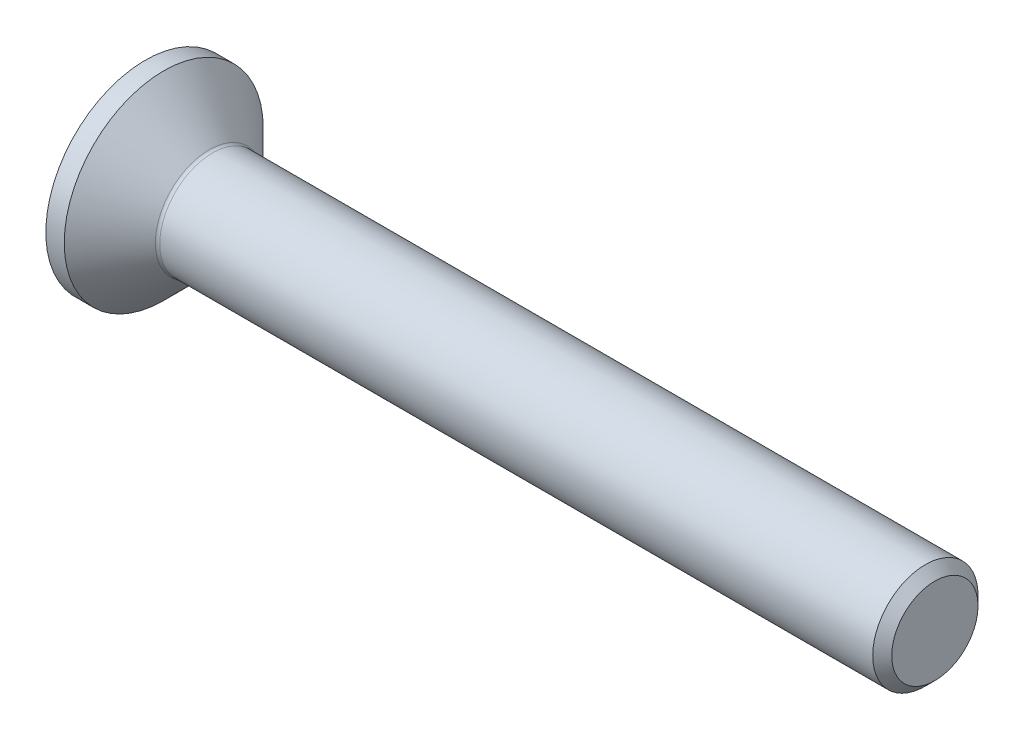
SolidWorks part; units mm, degrees
ref_plane "Front" through (0, 0, 0) normal (0, 0, 1) x (1, 0, 0)
ref_plane "Top" through (0, 0, 0) normal (0, 1, 0) x (1, 0, 0)
ref_plane "Right" through (0, 0, 0) normal (1, 0, 0) x (0, 0, -1)
sketch "Sketch1" plane through (0, 0, 0) normal (0, 0, 1) x (1, 0, 0)
  line L0 (0, 0) -> (0, 6.72)
  line L1 (0, 6.72) -> (3.72, 3)
  line L2 (3.72, 3) -> (45, 3)
  line L3 (45, 3) -> (45, 0)
  line L4 (45, 0) -> (0, 0)
  line L5 (-0.5871, 0) -> (5.4927, 0) construction
  dimension "l" = 45
  dimension "k" = 3.72
  dimension "d" = 6
  dimension "D1" = 45
revolve "Base" add sketch "Sketch1" angle 360 about L5
cosmetic thread "ThreadCosmetic1" parameters "b"=24, "D2"=4.917
sketch "Sketch2" plane through (0, 0, 0) normal (1, 0, 0) x (0, 0, -1)
  line L1 (2.3094, 0) -> (1.1547, 2)
  line L2 (1.1547, 2) -> (-1.1547, 2)
  line L3 (-1.1547, 2) -> (-2.3094, 0)
  line L4 (-2.3094, 0) -> (-1.1547, -2)
  line L5 (-1.1547, -2) -> (1.1547, -2)
  line L6 (1.1547, -2) -> (2.3094, 0)
  circle A0 centre (0, 0) radius 2 construction
  dimension "s" = 4
extrude "HexagonSocket" cut sketch "Sketch2" along normal blind 2.2
sketch "Sketch3" plane through (0, 0, 0) normal (0, 0, 1) x (1, 0, 0)
  line L0 (-0.4391, 0) -> (4.425, 0) construction
  line L1 (2.2, 0) -> (2.2, -2) construction
  line L2 (2.2, 2) -> (3.3547, 0)
  line L3 (3.3547, 0) -> (2.2, -2) construction
  line L4 (2.2, 2) -> (2.2, 0)
  line L5 (2.2, 0) -> (3.3547, 0)
  line L7 (2.2, 2) -> (2.2, 0) construction
  dimension "D1" = 120
revolve "Cut-Revolve1" cut sketch "Sketch3" angle 360 about L0
fillet "HeadFillet" radius 0.25 1 edges at (3.72, 0, 3)
chamfer "Chamfer" distance 0.5415 angle 45 1 edges at (45, 0, 3)
sketch "Sketch4" plane through (0, 0, 0) normal (0, 1, 0) x (1, 0, 0)
  line L0 (11.8531, 0) -> (-2.694, 0) construction
  line L1 (-2, 10.67) -> (3, 10.67)
  line L2 (-2, 10.67) -> (-2, 5.67)
  line L3 (-2, 5.67) -> (3, 5.67)
  line L4 (3, 10.67) -> (3, 5.67)
  line L5 (0, 6.72) -> (0, -6.72) construction
  dimension "dk" = 11.34
  dimension "D2" = 2
  dimension "D3" = 5
  dimension "D4" = 5
revolve "Cut-Revolve2" cut sketch "Sketch4" angle 360 about L0
sketch "Sketch5" plane through (0, 0, 0) normal (0, 0, 1) x (1, 0, 0)
  line L0 (44.4585, 2.531) -> (44.7292, 3)
  line L1 (44.7292, 3) -> (44.7292, 3.5415)
  line L2 (44.7292, 3.5415) -> (44.1877, 3.5415)
  line L3 (44.1877, 3.5415) -> (44.1877, 3)
  line L4 (44.1877, 3) -> (44.4585, 2.531)
  line L5 (0, 0) -> (10.6885, 0) construction
  line L6 (44.4585, 3) -> (44.4585, -3) construction
  dimension "D1" = 6
  dimension "D2" = 0.5415
revolve "Cut-Revolve10" [suppressed] cut sketch "Sketch5" angle 360 about L5
pattern_linear "LPattern10" [suppressed] count 37 spacing 0.6498 along (1, 0, 0)
equation "\"D1@Chamfer\" = (  \"d@Sketch1\" - \"D2@ThreadCosmetic1\" )  / 2"
equation "\"D1@Sketch5\" = \"d@Sketch1\""
equation "\"D2@Sketch5\" =  ( \"d@Sketch1\" - \"D2@ThreadCosmetic1\" )  / 2"
equation "\"D3@LPattern10\" = \"D2@Sketch5\" * 1.2"
equation "\"D1@LPattern10\" = \"b@ThreadCosmetic1\" / \"D3@LPattern10\""
